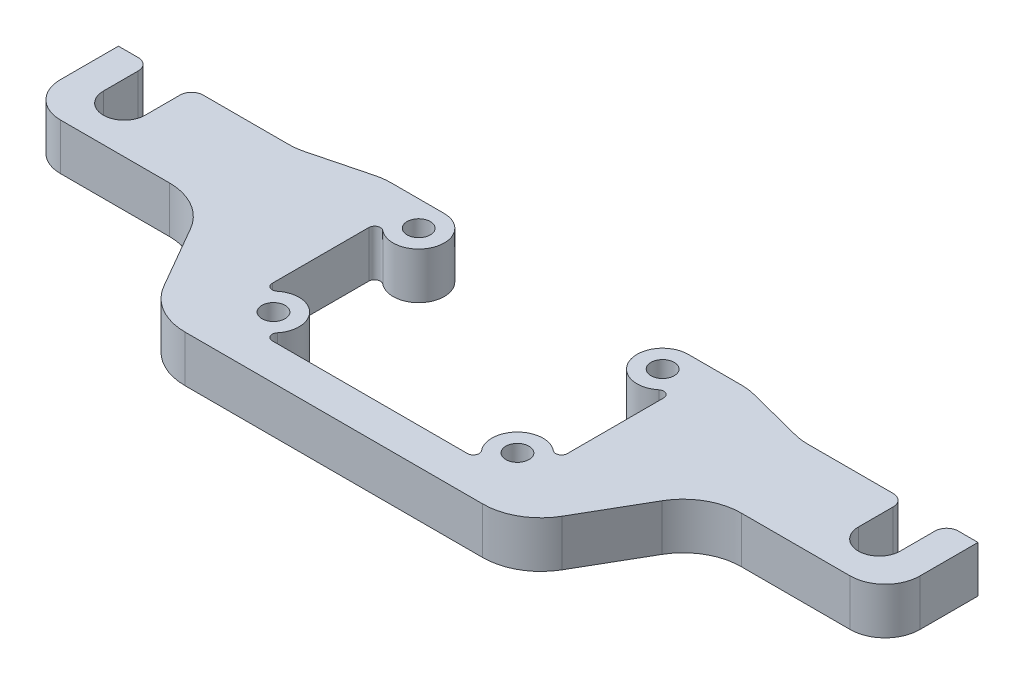
SolidWorks part; units mm, degrees
material "PLA"
ref_plane "Front Plane" through (0, 0, 0) normal (0, 0, 1) x (1, 0, 0)
ref_plane "Top Plane" through (0, 0, 0) normal (0, 1, 0) x (1, 0, 0)
ref_plane "Right Plane" through (0, 0, 0) normal (1, 0, 0) x (0, 0, -1)
sketch "Sketch1" plane through (0, 0, 0) normal (0, 0, 1) x (1, 0, 0)
  line L0 (0, 0) -> (0, 4)
  line L1 (0, 4) -> (-37, 4)
  line L7 (-37, 0) -> (0, 0)
  line L8 (0, 4) -> (0, 20.1474) construction
  line L9 (-37, 4) -> (-37, 0)
  dimension "D1" = 74
  dimension "D4" = 4
extrude "Boss-Extrude1" add sketch "Sketch1" against normal mid plane 20
sketch "Sketch2" plane through (0, 0, 0) normal (0, -1, 0) x (1, 0, 0)
  line L0 (-12.7, -7.8) -> (-12.7, 4.7)
  line L1 (-37, -10) -> (0, -10) construction
  line L2 (-10.5, -10) -> (-15.7, -10)
  line L3 (-15.7, -10) -> (-21.7333, -8.45)
  line L4 (-21.7333, -8.45) -> (-37, -8.45)
  line L6 (-37, -8.45) -> (-37, -0.45)
  line L7 (-37, -0.45) -> (-21.7333, -0.45)
  line L8 (-21.7333, -0.45) -> (-15.7, 10)
  line L9 (-15.7, 10) -> (0, 10)
  line L10 (0, 10) -> (0, 6.9)
  line L11 (0, -10) -> (0, 10) construction
  line L12 (0, 6.9) -> (-10.5, 6.9)
  line L13 (0, 6.9) -> (0, -17.6604) construction
  line L14 (-37, -10) -> (-37, 10) construction
  arc A0 (-12.7, -7.8) -> (-10.5, -10) centre (-10.5, -7.8) cw
  arc A1 (-12.7, 4.7) -> (-10.5, 6.9) centre (-10.5, 4.7) ccw
  point P9 (-37, -4.45)
  dimension "D4" = 2.2
  dimension "D1" = 2.2
  dimension "D2" = 2.2
  dimension "D3" = 21
  dimension "D5" = 12.5
  dimension "D6" = 3.35
  dimension "D7" = 8
  dimension "D8" = 3
  dimension "D9" = 60
extrude "Cut-Extrude1" cut sketch "Sketch2" against normal blind 20 flip side to cut contours L8 L9 L10 L12 A1 L0 A0 L2 L3 L4 L6 L7
hole_wizard "Ø2.0mm Dowel Hole1" positions "Sketch8" profile "Sketch10" hole size "Ø2.0" standard "ISO" end condition through all
sketch "Sketch8" plane through (0, 0, 0) normal (0, -1, 0) x (-1, 0, 0)
  arc A0 (10.5, 10) -> (12.7, 7.8) centre (10.5, 7.8) ccw construction
  arc A1 (12.7, -4.7) -> (10.5, -6.9) centre (10.5, -4.7) ccw construction
  point P0 (10.5, -4.7)
  point P2 (10.5, 7.8)
sketch "Sketch10" plane through (-10.5, 0, 4.7) normal (1, 0, 0) x (0, 0, -1)
  line L0 (0, 0) -> (0, 4)
  line L1 (0, 4) -> (1, 4)
  line L2 (1, 4) -> (1, 0)
  line L5 (1, 0) -> (0, 0)
  line L11 (0, -6.35) -> (0, 107.95) construction
  dimension "Thru Hole Dia." = 2
  dimension "Thru Hole Depth" = 4
hole_wizard "M3 Clearance Hole1" positions "Sketch11" profile "Sketch13" hole size "M3" standard "ISO"
sketch "Sketch11" plane through (0, 0, 0) normal (0, -1, 0) x (-1, 0, 0)
  line L0 (0, 0) -> (0, 15.8154) construction
  line L1 (37, 8.45) -> (37, 0.45) construction
  point P0 (32.5, 4.45)
  point P15 (37, 4.45)
  dimension "D1" = 65
sketch "Sketch13" plane through (-32.5, 0, -4.45) normal (1, 0, 0) x (0, 0, -1)
  line L0 (0, 0) -> (0, 5.0815)
  line L1 (0, 5.0815) -> (1.8, 4)
  line L2 (1.8, 4) -> (1.8, 0)
  line L5 (1.8, 0) -> (0, 0)
  line L10 (0, 5.0815) -> (-1.8, 4) construction
  line L11 (0, -6.35) -> (0, 107.95) construction
  dimension "Hole Dia." = 3.6
  dimension "Hole Depth" = 4
  dimension "Drill Angle" = 118
fillet "Fillet2" radius 3 1 edges at (-37, 2, -0.45)
fillet "Fillet3" radius 5 4 edges at (-15.7, 2, -10) (-21.7333, 2, -8.45) (-15.7, 2, 10) (-21.7333, 2, -0.45)
fillet "Fillet5" radius 0.5 3 edges at (-10.5, 2, 6.9) (-12.7, 2, 4.7) (-12.7, 2, -7.8)
sketch "Sketch14" plane through (0, 0, 0) normal (0, -1, 0) x (1, 0, 0)
  line L0 (-34.3, -4.45) -> (-34.3, -8.45)
  line L1 (-22.3653, -8.45) -> (-37, -8.45) construction
  line L2 (-34.3, -8.45) -> (-30.7, -8.45)
  line L3 (-30.7, -8.45) -> (-30.7, -4.45)
  line L4 (-34.3, -4.45) -> (-30.7, -4.45)
  circle A0 centre (-32.5, -4.45) radius 1.8 construction
extrude "Cut-Extrude2" cut sketch "Sketch14" against normal up to next
fillet "Fillet6" radius 1 2 edges at (-34.3, 2, -8.45) (-30.7, 2, -8.45)
mirror "Mirror1" about plane through (0, 0, -10) normal (1, 0, 0) of bodies 107 102
other "Freeze***"
